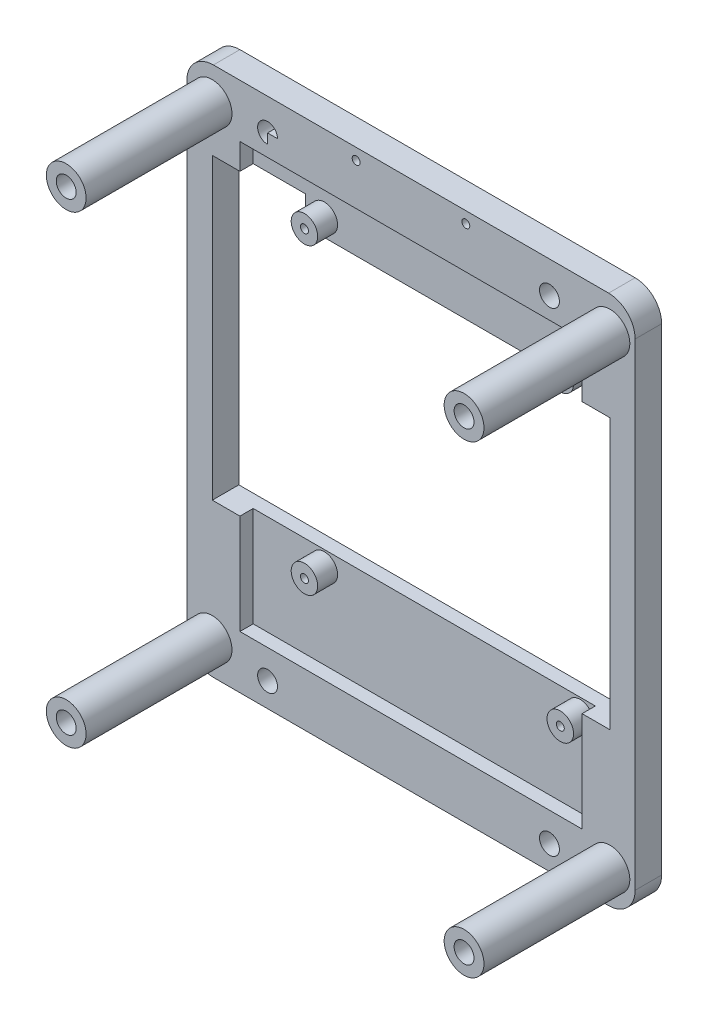
SolidWorks part; units mm, degrees
ref_plane "Front Plane" through (0, 0, 0) normal (0, 0, 1) x (1, 0, 0)
ref_plane "Top Plane" through (0, 0, 0) normal (0, 1, 0) x (1, 0, 0)
ref_plane "Right Plane" through (0, 0, 0) normal (1, 0, 0) x (0, 0, -1)
sketch "Sketch1" plane through (0, 0, 0) normal (0, 0, 1) x (1, 0, 0)
  line L1 (42.926, -50.8) -> (-42.926, -50.8)
  line L2 (42.926, -50.8) -> (42.926, 50.8)
  line L3 (42.926, 50.8) -> (-42.926, 50.8)
  line L4 (-42.926, -50.8) -> (-42.926, 50.8)
  line L5 (42.926, -50.8) -> (-42.926, 50.8) construction
  line L6 (42.926, 50.8) -> (-42.926, -50.8) construction
  point P0 (0, 0)
  dimension "D1" = 85.852
  dimension "D2" = 101.6
extrude "Boss-Extrude1" add sketch "Sketch1" along normal blind 12.7
shell "Shell1" thickness 10.16
sketch "Sketch3" plane through (0, 0, 10.16) normal (0, 0, 1) x (1, 0, 0)
  line L14 (-19.1392, -24.3938) -> (-19.1392, 33.6062) construction
  line L18 (-19.1392, 33.6062) -> (29.8608, -24.3938) construction
  line L19 (29.8608, -24.3938) -> (29.8608, 33.6062) construction
  circle A0 centre (-19.1392, 33.6062) radius 2.54
  circle A1 centre (29.8608, 33.6062) radius 2.54
  circle A2 centre (29.8608, -24.3938) radius 2.54
  circle A3 centre (-19.1392, -24.3938) radius 2.54
  circle A4 centre (-19.1392, 33.6062) radius 0.762
  circle A6 centre (29.8608, 33.6062) radius 0.762
  circle A7 centre (29.8608, -24.3938) radius 0.762
  circle A8 centre (-19.1392, -24.3938) radius 0.762
  dimension "D1" = 5.08
  dimension "D2" = 1.524
extrude "Boss-Extrude7" add sketch "Sketch3" along normal blind 3.81
fillet "Fillet1" radius 5.08 4 edges at (-42.926, -50.8, 6.35) (42.926, -50.8, 6.35) (42.926, 50.8, 6.35) (-42.926, 50.8, 6.35)
sketch "Sketch7" plane through (0, 0, 0) normal (0, 0, -1) x (-1, 0, 0)
  line L4 (-37.846, -50.8) -> (37.846, -50.8)
  line L5 (42.926, -45.72) -> (42.926, 45.72)
  line L6 (37.846, 50.8) -> (-37.846, 50.8)
  line L7 (-42.926, 45.72) -> (-42.926, -45.72)
  line L8 (-37.846, -50.8) -> (37.846, -50.8)
  line L9 (42.926, -45.72) -> (42.926, 45.72)
  line L10 (37.846, 50.8) -> (-37.846, 50.8)
  line L11 (-42.926, 45.72) -> (-42.926, -45.72)
  arc A4 (37.846, -50.8) -> (42.926, -45.72) centre (37.846, -45.72) ccw
  arc A5 (42.926, 45.72) -> (37.846, 50.8) centre (37.846, 45.72) ccw
  arc A6 (-37.846, 50.8) -> (-42.926, 45.72) centre (-37.846, 45.72) ccw
  arc A7 (-42.926, -45.72) -> (-37.846, -50.8) centre (-37.846, -45.72) ccw
  arc A8 (37.846, -50.8) -> (42.926, -45.72) centre (37.846, -45.72) ccw
  arc A9 (42.926, 45.72) -> (37.846, 50.8) centre (37.846, 45.72) ccw
  arc A10 (-37.846, 50.8) -> (-42.926, 45.72) centre (-37.846, 45.72) ccw
  arc A11 (-42.926, -45.72) -> (-37.846, -50.8) centre (-37.846, -45.72) ccw
  dimension "D1" = 0
extrude "Cut-Extrude4" cut sketch "Sketch7" against normal blind 7.62
sketch "Sketch8" plane through (0, 0, 12.7) normal (0, 0, 1) x (1, 0, 0)
  line L4 (-42.926, 45.72) -> (-42.926, -45.72)
  line L5 (-37.846, -50.8) -> (37.846, -50.8)
  line L6 (42.926, -45.72) -> (42.926, 45.72)
  line L7 (37.846, 50.8) -> (-37.846, 50.8)
  line L8 (-42.926, 45.72) -> (-42.926, -45.72)
  line L9 (-37.846, -50.8) -> (37.846, -50.8)
  line L10 (42.926, -45.72) -> (42.926, 45.72)
  line L11 (37.846, 50.8) -> (-37.846, 50.8)
  arc A4 (-42.926, -45.72) -> (-37.846, -50.8) centre (-37.846, -45.72) ccw
  arc A5 (37.846, -50.8) -> (42.926, -45.72) centre (37.846, -45.72) ccw
  arc A6 (42.926, 45.72) -> (37.846, 50.8) centre (37.846, 45.72) ccw
  arc A7 (-37.846, 50.8) -> (-42.926, 45.72) centre (-37.846, 45.72) ccw
  arc A8 (-42.926, -45.72) -> (-37.846, -50.8) centre (-37.846, -45.72) ccw
  arc A9 (37.846, -50.8) -> (42.926, -45.72) centre (37.846, -45.72) ccw
  arc A10 (42.926, 45.72) -> (37.846, 50.8) centre (37.846, 45.72) ccw
  arc A11 (-37.846, 50.8) -> (-42.926, 45.72) centre (-37.846, 45.72) ccw
  dimension "D1" = 0
sketch "Sketch10" plane through (0, 0, 12.7) normal (0, 0, 1) x (1, 0, 0)
  line L1 (-38.1, 44.45) -> (38.1, 44.45) construction
  line L2 (-38.1, 44.45) -> (-38.1, -44.45) construction
  line L3 (-38.1, -44.45) -> (38.1, -44.45) construction
  line L4 (38.1, 44.45) -> (38.1, -44.45) construction
  line L5 (-38.1, 44.45) -> (38.1, -44.45) construction
  line L6 (-38.1, -44.45) -> (38.1, 44.45) construction
  circle A0 centre (-38.1, 44.45) radius 3.81
  circle A1 centre (38.1, 44.45) radius 3.81
  circle A2 centre (38.1, -44.45) radius 3.81
  circle A3 centre (-38.1, -44.45) radius 3.81
  circle A4 centre (-38.1, 44.45) radius 1.905
  circle A5 centre (38.1, 44.45) radius 1.905
  circle A6 centre (38.1, -44.45) radius 1.905
  circle A7 centre (-38.1, -44.45) radius 1.905
  point P0 (0, 0)
  dimension "D1" = 7.62
  dimension "D3" = 3.81
extrude "Boss-Extrude6" add sketch "Sketch10" along normal blind 27.94 contours A0 A4 | A1 A5 | A2 A6 | A3 A7
sketch "Sketch11" plane through (0, 0, 0) normal (0, 0, 1) x (1, 0, 0)
  line L0 (0, 0) -> (0.0456, -21.4976) construction
  line L3 (-38.0544, -21.4976) -> (38.1456, -21.4976)
  line L4 (38.1456, 30.2511) -> (38.1456, -21.4976)
  line L6 (-22.7065, 30.2511) -> (-22.7065, 35.6891)
  line L9 (-22.7065, 30.2511) -> (38.1456, 30.2511)
  line L10 (-38.0544, -21.4976) -> (-38.0544, 35.6891)
  line L11 (-38.0544, 35.6891) -> (-22.7065, 35.6891)
  dimension "D1" = 76.2
extrude "Cut-Extrude5" cut sketch "Sketch11" along normal blind 83.058
sketch "Sketch13" plane through (0, 0, 12.7) normal (0, 0, 1) x (1, 0, 0)
  line L0 (0, 50.8) -> (0, 48.6302) construction
  line L1 (37.846, 50.8) -> (-37.846, 50.8) construction
  line L2 (-10.5, 48.6302) -> (10.5, 48.6302) construction
  line L4 (-27.4773, 44.7073) -> (26.5207, 44.7073)
  line L5 (-27.4773, 44.7073) -> (-27.4773, -46.1875)
  line L6 (-27.4773, -46.1875) -> (26.5207, -46.1875)
  line L7 (26.5207, 44.7073) -> (26.5207, -46.1875)
  circle A0 centre (10.5, 48.6302) radius 0.762
  circle A1 centre (-10.5, 48.6302) radius 0.762
  circle A3 centre (-27.4773, 44.7073) radius 1.905
  circle A4 centre (26.5207, 44.7073) radius 1.905
  circle A5 centre (-27.4773, -46.1875) radius 1.905
  circle A6 centre (26.5207, -46.1875) radius 1.905
  dimension "D1" = 3.81
extrude "Cut-Extrude6" cut sketch "Sketch13" against normal blind 9.906 contours L7 A4 L4 | L4 A4 L7 | A0 | A1 | L4 A3 L5 | L7 A6 L6 | L5 A5 L6 | L6 A5 L5 | L6 A6 L7
